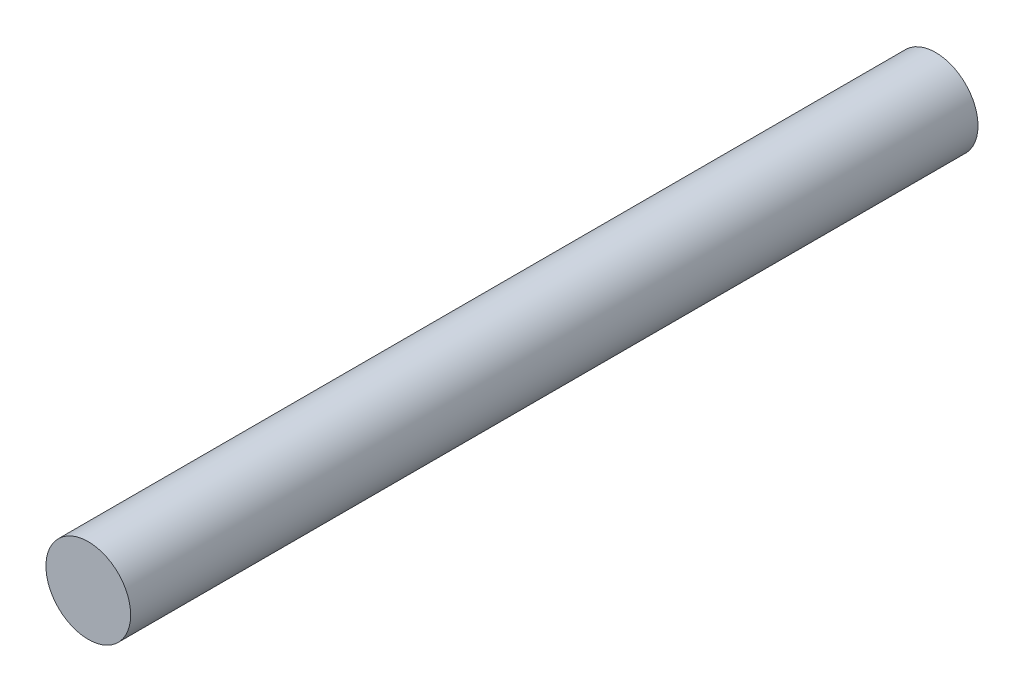
SolidWorks part; units mm, degrees
ref_plane "Plan de face" through (0, 0, 0) normal (0, 0, 1) x (1, 0, 0)
ref_plane "Plan de dessus" through (0, 0, 0) normal (0, 1, 0) x (1, 0, 0)
ref_plane "Plan de droite" through (0, 0, 0) normal (1, 0, 0) x (0, 0, -1)
sketch "Esquisse1" plane through (0, 0, 0) normal (0, 0, 1) x (1, 0, 0)
  circle A0 centre (0, 0) radius 2.5
extrude "Boss.-Extru.1" add sketch "Esquisse1" along normal blind 50
